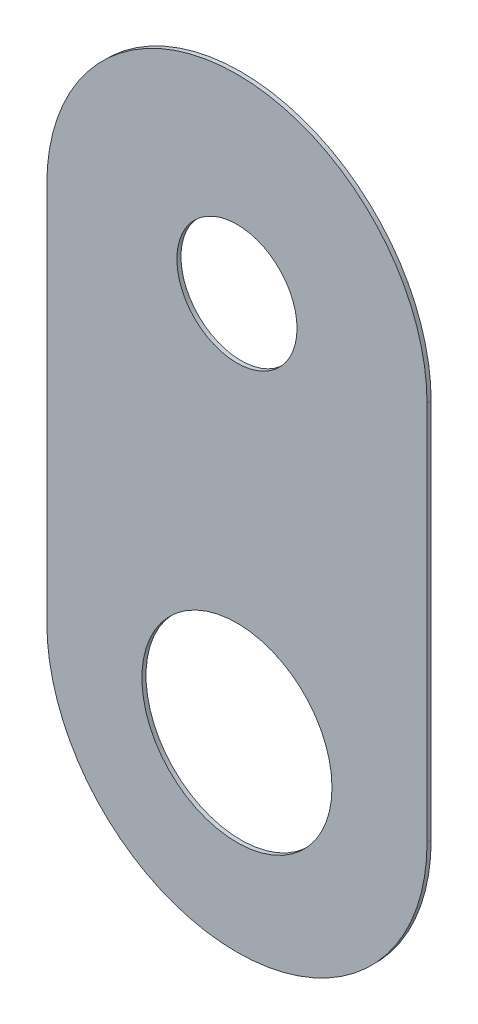
SolidWorks part; units mm, degrees
ref_plane "Front Plane" through (0, 0, 0) normal (0, 0, 1) x (1, 0, 0)
ref_plane "Top Plane" through (0, 0, 0) normal (0, 1, 0) x (1, 0, 0)
ref_plane "Right Plane" through (0, 0, 0) normal (1, 0, 0) x (0, 0, -1)
sketch "Sketch1" plane through (0, 0, 0) normal (0, 0, 1) x (1, 0, 0)
  line L0 (0, 0) -> (0, 50.8)
  line L2 (50.8, 50.8) -> (50.8, 0)
  arc A0 (0, 50.8) -> (50.8, 50.8) centre (25.4, 50.8) cw
  arc A1 (50.8, 0) -> (0, 0) centre (25.4, 0) cw
  dimension "D1" = 101.6
  dimension "D2" = 50.8
extrude "Boss-Extrude1" add sketch "Sketch1" along normal blind 0.5499
sketch "Sketch2" plane through (0, 0, 0.5499) normal (0, 0, 1) x (1, 0, 0)
  line L0 (25.4, 76.2) -> (25.4, -25.4) construction
  line L1 (0, 50.8) -> (50.8, 50.8) construction
  line L2 (0, 0) -> (50.8, 0) construction
  arc A1 (50.8, 50.8) -> (0, 50.8) centre (25.4, 50.8) ccw construction
  arc A2 (0, 0) -> (50.8, 0) centre (25.4, 0) ccw construction
  circle A3 centre (25.4, 0) radius 12.7
  circle A4 centre (25.4, 50.8) radius 8.0264
  dimension "D1" = 16.0528
  dimension "D2" = 25.4
extrude "Cut-Extrude2" cut sketch "Sketch2" against normal through all
equation "\"L\"= 4in"
equation "\"F\"= 650"
equation "\"W\"= 2in"
equation "\"WT\"= 1in"
equation "\"SY\" = 120091"
equation "\"SF\"= 4"
equation "\"T\"= ( \"F\" * \"SF\" ) / ( \"WT\" * \"SY\" )"
equation "\"D1@Sketch1\"= \"L\""
equation "\"D2@Sketch1\"= \"W\""
equation "\"D1@Boss-Extrude1\"=\"T\""
